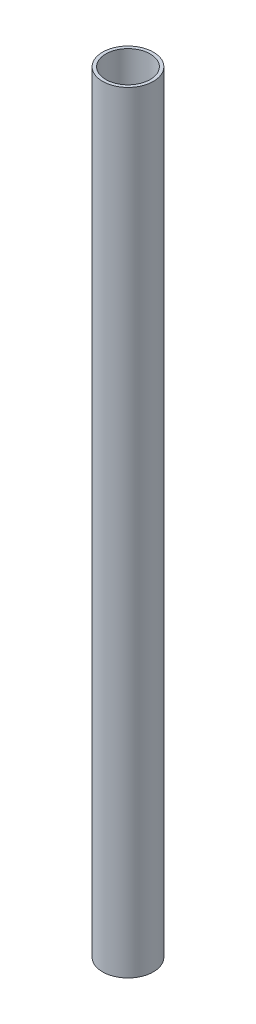
SolidWorks part; units mm, degrees
ref_plane "Front Plane" through (0, 0, 0) normal (0, 0, 1) x (1, 0, 0)
ref_plane "Top Plane" through (0, 0, 0) normal (0, 1, 0) x (1, 0, 0)
ref_plane "Right Plane" through (0, 0, 0) normal (1, 0, 0) x (0, 0, -1)
sketch "Sketch1" plane through (0, 0, 0) normal (0, 1, 0) x (1, 0, 0)
  circle A0 centre (0, 0) radius 8
  circle A1 centre (0, 0) radius 7
extrude "Boss-Extrude1" add sketch "Sketch1" along normal blind 243.065
